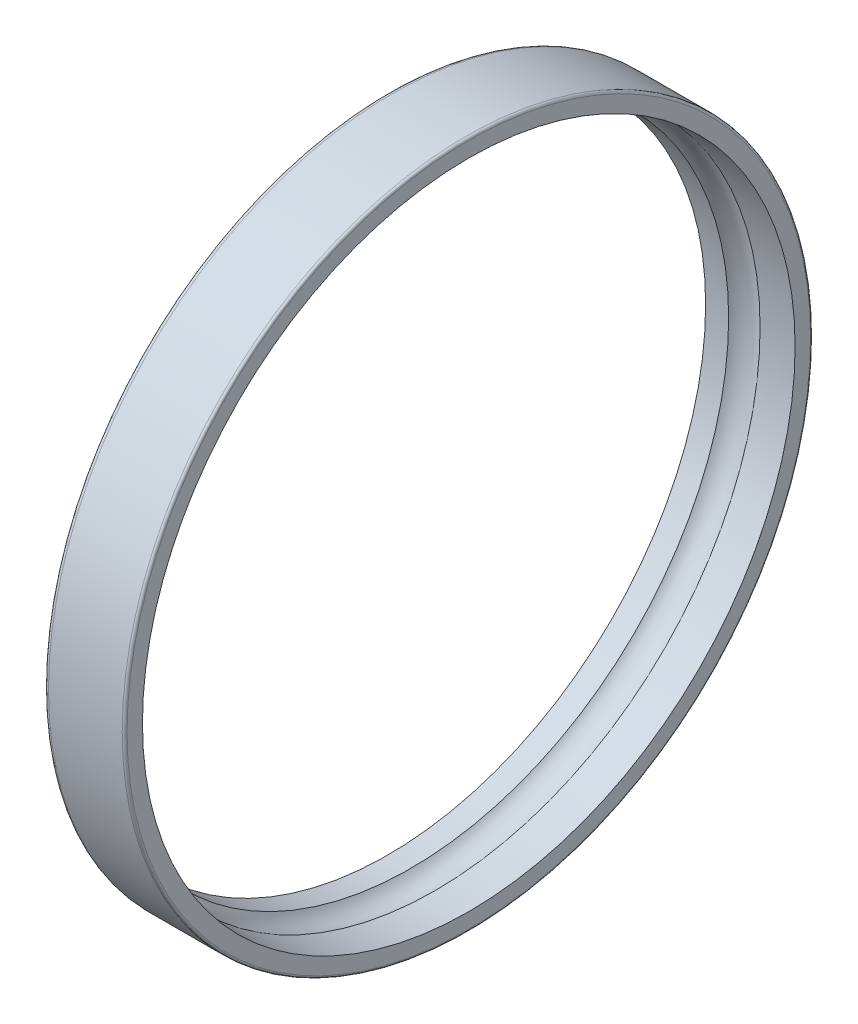
SolidWorks part; units mm, degrees
material "1.7016 (17Cr3)"
ref_plane "Front Plane" through (0, 0, 0) normal (0, 0, 1) x (1, 0, 0)
ref_plane "Top Plane" through (0, 0, 0) normal (0, 1, 0) x (1, 0, 0)
ref_plane "Right Plane" through (0, 0, 0) normal (1, 0, 0) x (0, 0, -1)
sketch "草图1" plane through (0, 0, 0) normal (0, 0, 1) x (1, 0, 0)
  line L0 (9.7, 42.5) -> (0.6, 42.5)
  line L1 (0, 41.9) -> (0, 39.25)
  line L2 (0, 39.25) -> (2.8425, 39.25)
  line L3 (5.8205, 40.1541) -> (10, 40.3)
  line L4 (10, 40.3) -> (10, 42.2)
  line L5 (-0.0013, 0) -> (10.0013, 0) construction
  arc A0 (0.6, 42.5) -> (0, 41.9) centre (0.6, 41.9) ccw
  arc A1 (2.8425, 39.25) -> (5.8205, 40.1541) centre (5, 37.5) cw
  arc A2 (10, 42.2) -> (9.7, 42.5) centre (9.7, 42.2) ccw
revolve "旋转1" add sketch "草图1" angle 360 about L5
